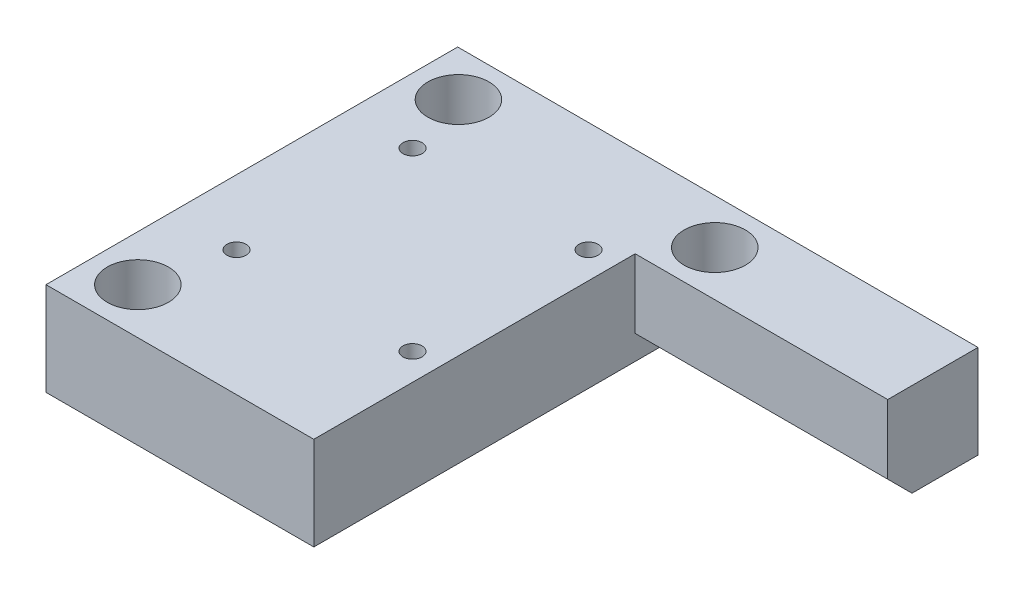
SolidWorks part; units mm, degrees
material "6061 Alloy"
ref_plane "Front" through (0, 0, 0) normal (0, 0, 1) x (1, 0, 0)
ref_plane "Top" through (0, 0, 0) normal (0, 1, 0) x (1, 0, 0)
ref_plane "Right" through (0, 0, 0) normal (1, 0, 0) x (0, 0, -1)
sketch "Sketch1" plane through (0, 0, 0) normal (0, 1, 0) x (1, 0, 0)
  line L0 (0, -53.8) -> (68, -53.8)
  line L1 (68, -53.8) -> (68, 0)
  line L2 (68, 0) -> (0, 0)
  line L3 (0, 0) -> (0, -53.8)
extrude "Boss-Extrude1" add sketch "Sketch1" against normal blind 12.192
sketch "Sketch2" plane through (0, -12.192, 0) normal (0, -1, 0) x (1, 0, 0)
  line L0 (35, 53.8) -> (35, 11.8)
  line L1 (35, 11.8) -> (68, 11.8)
  line L2 (68, 11.8) -> (68, 53.8)
  line L3 (68, 53.8) -> (35, 53.8)
extrude "Cut-Extrude1" cut sketch "Sketch2" against normal through all
hole_wizard "M3x0.5 Tapped Hole1" positions "Sketch4" profile "Sketch3" tap size "M3x0.5" standard "ANSI Metric" end condition through all
sketch "Sketch4" plane through (0, -12.192, 0) normal (0, -1, 0) x (-1, 0, 0)
  point P0 (-31.5022, -14.4024)
  point P1 (-31.5, -37.4046)
  point P2 (-8.5, -14.4002)
  point P3 (-8.4978, -37.4024)
sketch "Sketch3" plane through (31.5022, -12.192, 14.4024) normal (1, 0, 0) x (0, 0, -1)
  line L0 (0, 0) -> (0, 12.192)
  line L1 (0, 12.192) -> (1.25, 12.192)
  line L2 (1.25, 12.192) -> (1.25, 0)
  line L5 (1.25, 0) -> (0, 0)
  line L11 (0, -6.35) -> (0, 107.95) construction
  dimension "Thru Tap Drill Dia." = 2.5
  dimension "Thru Tap Drill Depth" = 12.192
hole_wizard "CBORE for M4 SHCS1" positions "Sketch6" profile "Sketch5" counterbore size "M4" standard "ANSI Metric" end condition through all
sketch "Sketch6" plane through (0, 0, 0) normal (0, 1, 0) x (1, 0, 0)
  point P0 (6, -47.8)
  point P1 (6, -5.9)
  point P2 (39.5, -5.9)
sketch "Sketch5" plane through (6, 0, 47.8) normal (1, 0, 0) x (0, 0, 1)
  line L0 (0, 0) -> (0, 12.192)
  line L1 (0, 12.192) -> (2.4, 12.192)
  line L3 (2.4, 12.192) -> (2.4, 7)
  line L4 (2.4, 7) -> (4, 7)
  line L5 (4, 7) -> (4, 0)
  line L7 (4, 0) -> (0, 0)
  line L11 (0, -6.35) -> (0, 107.95) construction
  dimension "Thru Hole Dia." = 4.8
  dimension "Thru Hole Depth" = 12.192
  dimension "C'Bore Dia." = 8
  dimension "C'Bore Depth" = 7
chamfer "Chamfer1" distance 3.175 angle 45 1 edges at (51.5, -12.192, 11.8)
